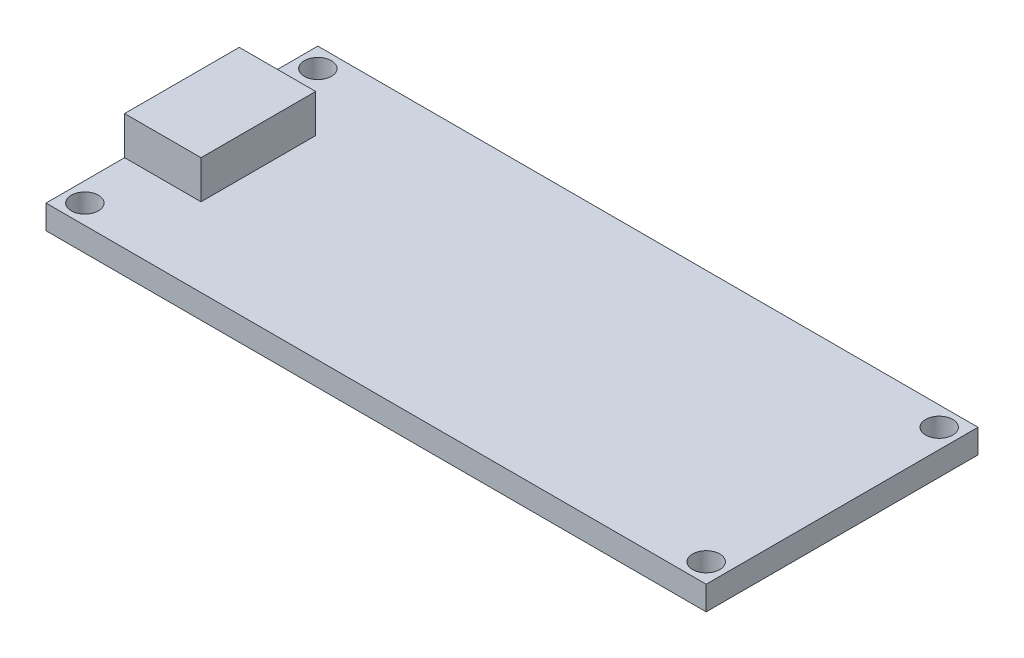
SolidWorks part; units mm, degrees
ref_plane "Front Plane" through (0, 0, 0) normal (0, 0, 1) x (1, 0, 0)
ref_plane "Top Plane" through (0, 0, 0) normal (0, 1, 0) x (1, 0, 0)
ref_plane "Right Plane" through (0, 0, 0) normal (1, 0, 0) x (0, 0, -1)
sketch "Sketch1" plane through (0, 0, 0) normal (0, 1, 0) x (1, 0, 0)
  line L1 (-38.6612, 0.923) -> (4.5188, 0.923)
  line L2 (-38.6612, 0.923) -> (-38.6612, 18.703)
  line L3 (-38.6612, 18.703) -> (4.5188, 18.703)
  line L4 (4.5188, 0.923) -> (4.5188, 18.703)
  circle A0 centre (-37.3912, 17.433) radius 0.889
  circle A1 centre (-37.3912, 2.193) radius 0.889
  circle A2 centre (3.2488, 2.193) radius 0.889
  circle A3 centre (3.2488, 17.433) radius 0.889
  dimension "D5" = 1.778
  dimension "D6" = 1.778
  dimension "D11" = 1.778
  dimension "D12" = 1.778
  dimension "D1" = 43.18
  dimension "D2" = 17.78
  dimension "D3" = 1.27
  dimension "D4" = 1.27
  dimension "D7" = 1.27
  dimension "D8" = 1.27
  dimension "D9" = 1.27
  dimension "D10" = 1.27
  dimension "D13" = 1.27
  dimension "D14" = 1.27
extrude "Boss-Extrude1" add sketch "Sketch1" along normal blind 1.57
sketch "Sketch2" plane through (0, 1.57, 0) normal (0, 1, 0) x (1, 0, 0)
  line L0 (-38.6612, 18.703) -> (-38.6612, 0.923) construction
  line L1 (-38.6612, 13.563) -> (-33.6612, 13.563)
  line L2 (-38.6612, 13.563) -> (-38.6612, 6.063)
  line L3 (-38.6612, 6.063) -> (-33.6612, 6.063)
  line L4 (-33.6612, 13.563) -> (-33.6612, 6.063)
  line L5 (-33.6612, 9.813) -> (-38.6612, 9.813)
  circle A1 centre (-37.3912, 17.433) radius 0.889 construction
  line M4 (-38.6612, 18.703) -> (-38.6612, 0.923)
  dimension "D1" = 5
  dimension "D2" = 7.5
  dimension "D3" = 7.62
extrude "Boss-Extrude2" add sketch "Sketch2" along normal blind 2.5 contours L5 L4 L1 M4 | L4 L5 L2 L3
